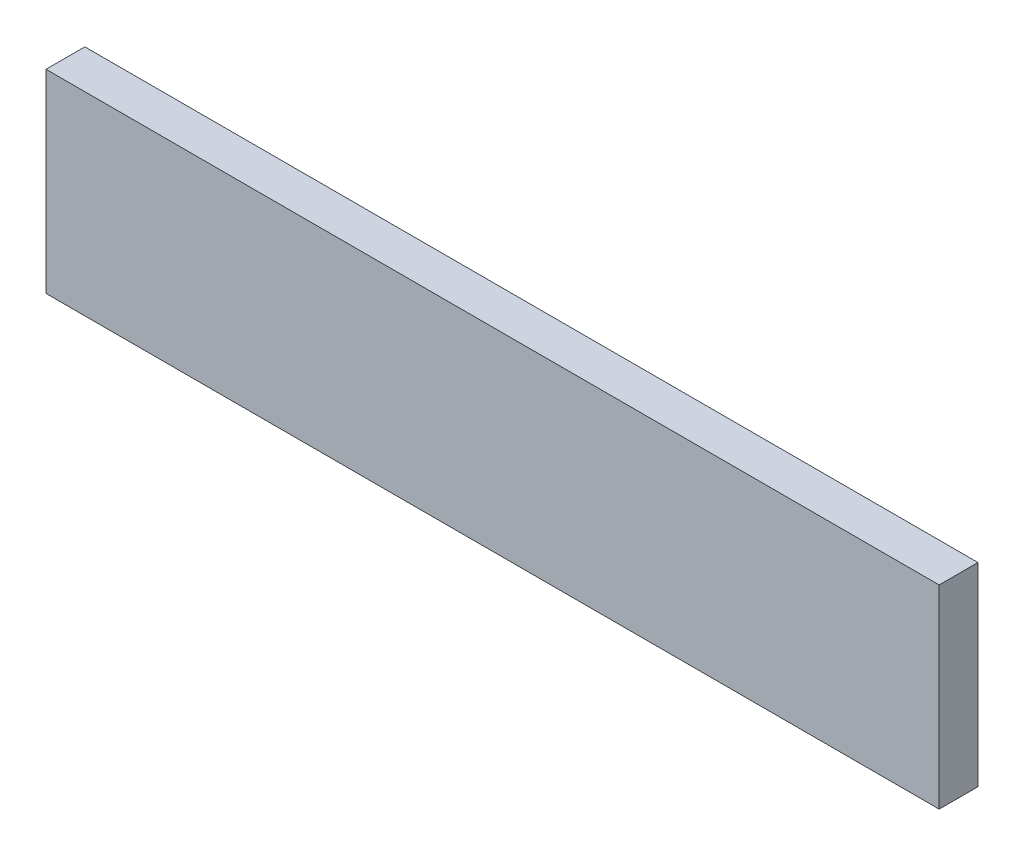
SolidWorks part; units mm, degrees
ref_plane "前视基准面" through (0, 0, 0) normal (0, 0, 1) x (1, 0, 0)
ref_plane "上视基准面" through (0, 0, 0) normal (0, 1, 0) x (1, 0, 0)
ref_plane "右视基准面" through (0, 0, 0) normal (1, 0, 0) x (0, 0, -1)
sketch "草图1" plane through (0, 0, 0) normal (0, 0, 1) x (1, 0, 0)
  line L1 (0, 0) -> (230, 0)
  line L2 (0, 0) -> (0, 50)
  line L3 (0, 50) -> (230, 50)
  line L4 (230, 0) -> (230, 50)
  dimension "D1" = 50
  dimension "D2" = 230
extrude "凸台-拉伸1" add sketch "草图1" along normal blind 10
